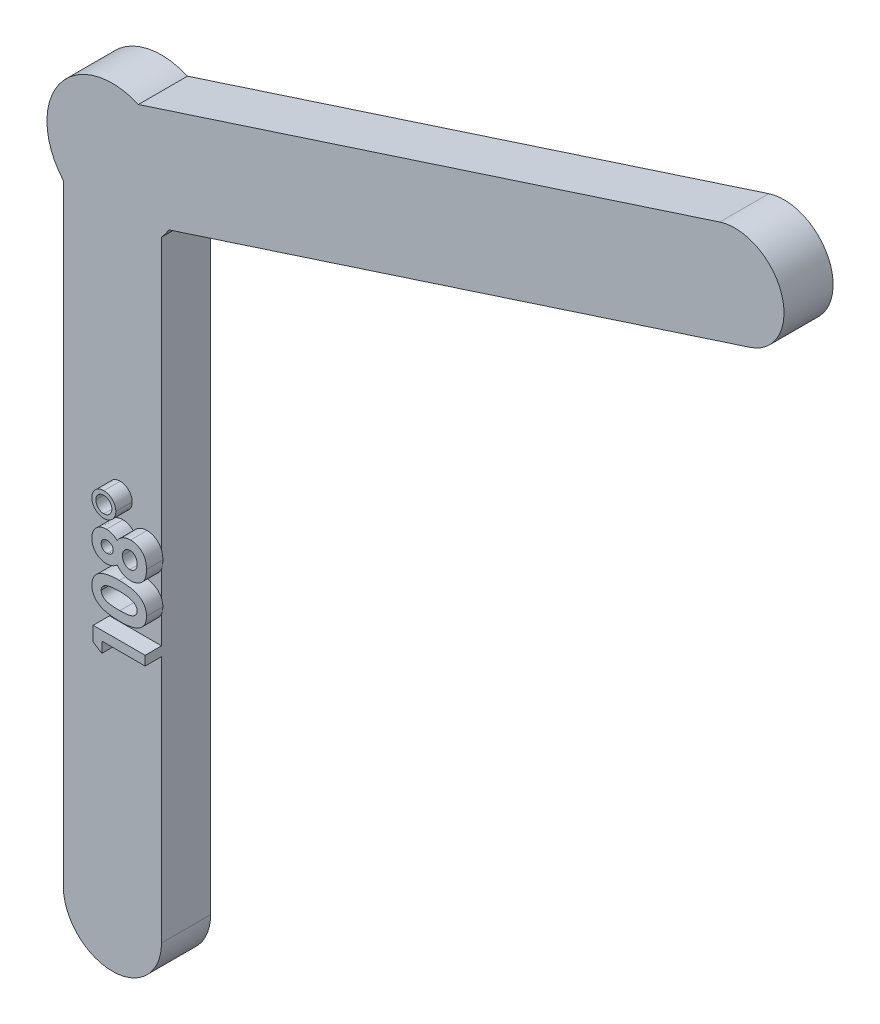
SolidWorks part; units mm, degrees
ref_plane "Front Plane" through (0, 0, 0) normal (0, 0, 1) x (1, 0, 0)
ref_plane "Top Plane" through (0, 0, 0) normal (0, 1, 0) x (1, 0, 0)
ref_plane "Right Plane" through (0, 0, 0) normal (1, 0, 0) x (0, 0, -1)
sketch "Sketch2" plane through (0, 0, 0) normal (0, 0, 1) x (1, 0, 0)
  line L0 (0, 0) -> (0, -40) construction
  line L1 (0, 0) -> (38.0423, 12.3607) construction
  line L2 (37.1152, 15.2138) -> (38.9693, 9.5075) construction
  line L3 (-3, -40) -> (3, -40) construction
  line L4 (-3, -40) -> (-3, -2.6458)
  line L5 (3, -40) -> (3, -2.6458)
  line L6 (37.1152, 15.2138) -> (1.5892, 3.6708)
  line L7 (38.9693, 9.5075) -> (3.4433, -2.0356)
  arc A0 (1.5892, 3.6708) -> (-3, -2.6458) centre (0, 0) ccw
  arc A1 (-3, -40) -> (3, -40) centre (0, -40) ccw
  arc A2 (37.1152, 15.2138) -> (38.9693, 9.5075) centre (38.0423, 12.3607) cw
  arc A3 (3, -2.6458) -> (3.4433, -2.0356) centre (0, 0) ccw
  point P12 (38.0423, 12.3607)
  dimension "D3" = 3
  dimension "D4" = 8
  dimension "D1" = 40
  dimension "D2" = 108
extrude "Boss-Extrude1" add sketch "Sketch2" along normal blind 3
sketch "Sketch3" plane through (0, 0, 3) normal (0, 0, 1) x (1, 0, 0)
  text T0 "<b>108°</b>"
extrude "Boss-Extrude2" add sketch "Sketch3" along normal blind 1
